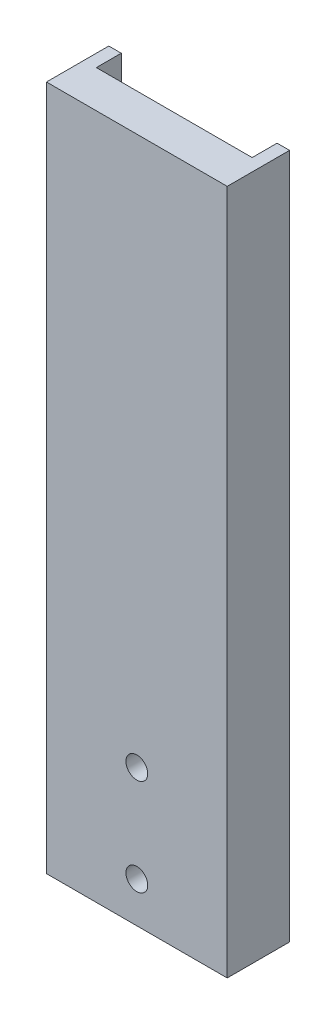
SolidWorks part; units mm, degrees
ref_plane "Front Plane" through (0, 0, 0) normal (0, 0, 1) x (1, 0, 0)
ref_plane "Top Plane" through (0, 0, 0) normal (0, 1, 0) x (1, 0, 0)
ref_plane "Right Plane" through (0, 0, 0) normal (1, 0, 0) x (0, 0, -1)
sketch "Sketch1" plane through (0, 0, 0) normal (0, 0, 1) x (1, 0, 0)
  line L1 (14.5, -55) -> (-14.5, -55)
  line L2 (14.5, -55) -> (14.5, 55)
  line L3 (14.5, 55) -> (-14.5, 55)
  line L4 (-14.5, -55) -> (-14.5, 55)
  line L5 (14.5, -55) -> (-14.5, 55) construction
  line L6 (14.5, 55) -> (-14.5, -55) construction
  point P0 (0, 0)
  dimension "D1" = 29
  dimension "D2" = 110
extrude "Boss-Extrude1" add sketch "Sketch1" along normal blind 10
sketch "Sketch2" plane through (0, 55, 0) normal (0, 1, 0) x (1, 0, 0)
  line L1 (0, 0) -> (0, -7.8795) construction
  line L5 (-12.5, 0) -> (-12.5, -4)
  line L6 (14.5, 0) -> (-14.5, 0) construction
  line L7 (-12.5, -4) -> (12.5, -4)
  line L8 (12.5, -4) -> (12.5, 0)
  line L9 (-12.5, 0) -> (12.5, 0)
  line L10 (-14.5, -10) -> (-14.5, 0) construction
  dimension "D1" = 4
  dimension "D2" = 2
extrude "Cut-Extrude1" cut sketch "Sketch2" against normal blind 50 and the other way through all
sketch "Sketch3" plane through (0, 0, 0) normal (0, 0, -1) x (-1, 0, 0)
  line L0 (0, -55) -> (0, -17.1251) construction
  line L1 (14.5, -55) -> (-14.5, -55) construction
  circle A0 centre (0, -48.5) radius 1.75
  circle A1 centre (0, -33) radius 1.75
  dimension "D1" = 3.5
  dimension "D2" = 6.5
  dimension "D3" = 3.5
  dimension "D4" = 15.5
extrude "Cut-Extrude2" cut sketch "Sketch3" against normal through all
sketch "Sketch4" plane through (0, 0, 10) normal (0, 0, 1) x (1, 0, 0)
  line L0 (-14.5, -55) -> (14.5, -55) construction
  line L1 (1.8764, -45.25) -> (-1.8764, -45.25)
  line L2 (-1.8764, -45.25) -> (-3.7528, -48.5)
  line L3 (-3.7528, -48.5) -> (-1.8764, -51.75)
  line L4 (-1.8764, -51.75) -> (1.8764, -51.75)
  line L5 (1.8764, -51.75) -> (3.7528, -48.5)
  line L6 (3.7528, -48.5) -> (1.8764, -45.25)
  line L7 (3.7528, -33) -> (1.8764, -29.75)
  line L8 (1.8764, -29.75) -> (-1.8764, -29.75)
  line L9 (-1.8764, -29.75) -> (-3.7528, -33)
  line L10 (-3.7528, -33) -> (-1.8764, -36.25)
  line L11 (-1.8764, -36.25) -> (1.8764, -36.25)
  line L12 (1.8764, -36.25) -> (3.7528, -33)
  circle A0 centre (0, -48.5) radius 3.25 construction
  circle A1 centre (0, -33) radius 3.25 construction
  dimension "D1" = 6.5
  dimension "D2" = 6.5
ref_plane "Plane1" through (0, 0, 5) normal (0, 0, 1) x (1, 0, 0)
sketch "Sketch5" plane through (0, 0, 0) normal (0, 0, -1) x (-1, 0, 0)
  line L0 (14.5, -55) -> (-14.5, -55) construction
  line L1 (1.8764, -51.75) -> (3.7528, -48.5)
  line L2 (3.7528, -48.5) -> (1.8764, -45.25)
  line L3 (1.8764, -45.25) -> (-1.8764, -45.25)
  line L4 (-1.8764, -45.25) -> (-3.7528, -48.5)
  line L5 (-3.7528, -48.5) -> (-1.8764, -51.75)
  line L6 (-1.8764, -51.75) -> (1.8764, -51.75)
  line L7 (1.8764, -36.25) -> (3.7528, -33)
  line L8 (3.7528, -33) -> (1.8764, -29.75)
  line L9 (1.8764, -29.75) -> (-1.8764, -29.75)
  line L10 (-1.8764, -29.75) -> (-3.7528, -33)
  line L11 (-3.7528, -33) -> (-1.8764, -36.25)
  line L12 (-1.8764, -36.25) -> (1.8764, -36.25)
  circle A0 centre (0, -48.5) radius 3.25 construction
  circle A1 centre (0, -33) radius 3.25 construction
  dimension "D1" = 6.5
  dimension "D2" = 6.5
extrude "Cut-Extrude3" cut sketch "Sketch5" against normal blind 3
